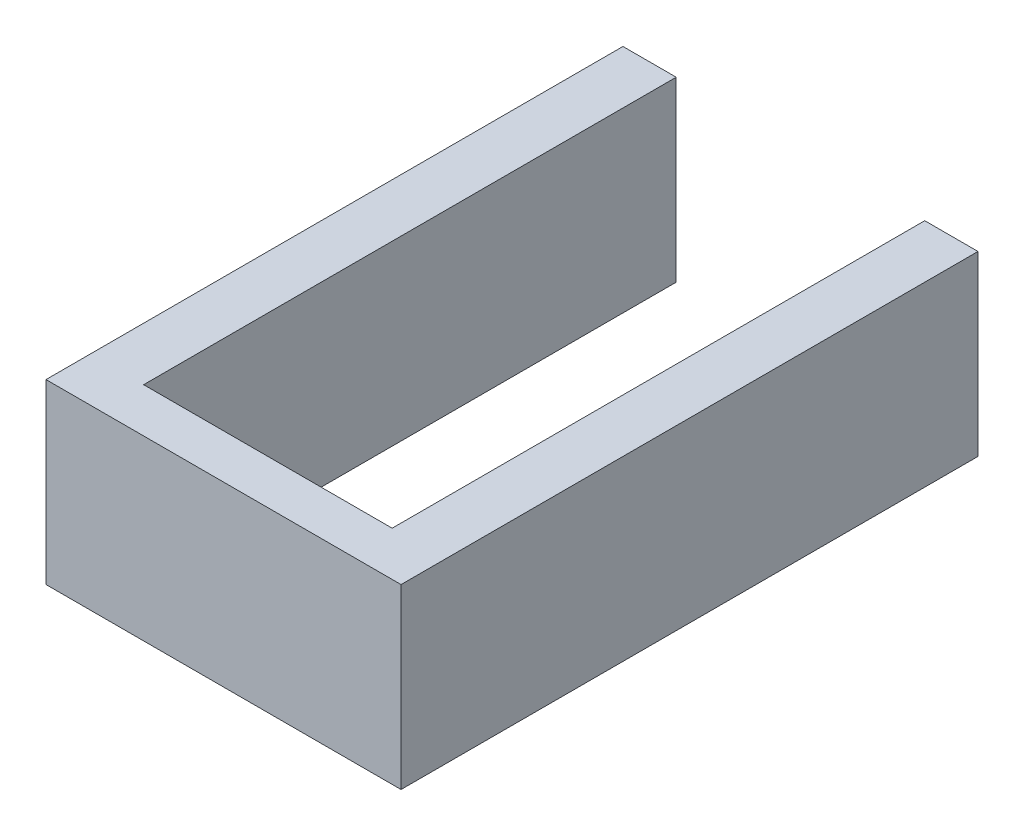
SolidWorks part; units mm, degrees
ref_plane "Front Plane" through (0, 0, 0) normal (0, 0, 1) x (1, 0, 0)
ref_plane "Top Plane" through (0, 0, 0) normal (0, 1, 0) x (1, 0, 0)
ref_plane "Right Plane" through (0, 0, 0) normal (1, 0, 0) x (0, 0, -1)
sketch "Sketch1" plane through (0, 0, 0) normal (0, 0, 1) x (1, 0, 0)
  line L1 (-18.9583, 10.6771) -> (21.0417, 10.6771)
  line L2 (-18.9583, 10.6771) -> (-18.9583, -9.3229)
  line L3 (-18.9583, -9.3229) -> (21.0417, -9.3229)
  line L4 (21.0417, 10.6771) -> (21.0417, -9.3229)
  dimension "D1" = 40
  dimension "D2" = 20
extrude "Boss-Extrude1" add sketch "Sketch1" along normal blind 5
sketch "Sketch2" plane through (0, 0, 0) normal (0, 0, -1) x (-1, 0, 0)
  line L0 (18.9583, -9.3229) -> (-21.0417, -9.3229) construction
  line L1 (-21.0417, 10.6771) -> (-15.0417, 10.6771)
  line L2 (-21.0417, 10.6771) -> (-21.0417, -9.3229)
  line L3 (-21.0417, -9.3229) -> (-15.0417, -9.3229)
  line L4 (-15.0417, 10.6771) -> (-15.0417, -9.3229)
  line L6 (18.9583, 10.6771) -> (12.9583, 10.6771)
  line L7 (18.9583, 10.6771) -> (18.9583, -9.3229)
  line L8 (18.9583, -9.3229) -> (12.9583, -9.3229)
  line L9 (12.9583, 10.6771) -> (12.9583, -9.3229)
  dimension "D1" = 6
  dimension "D2" = 6
extrude "Boss-Extrude2" add sketch "Sketch2" along normal blind 60
